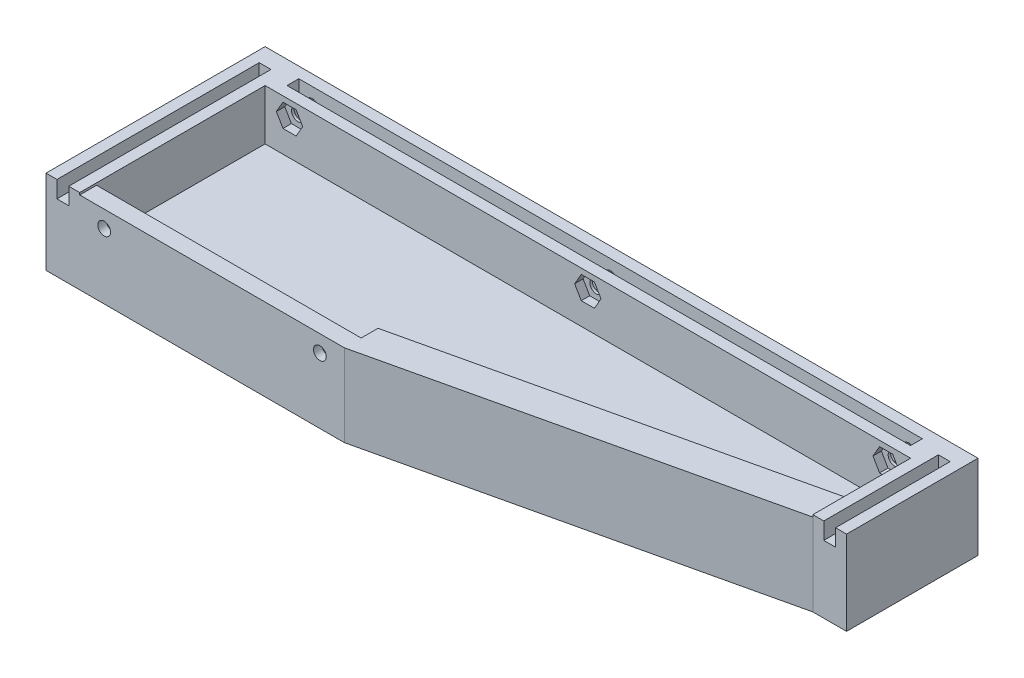
SolidWorks part; units mm, degrees
ref_plane "Front Plane" through (0, 0, 0) normal (1, 0, 0) x (0, 1, 0)
ref_plane "Top Plane" through (0, 0, 0) normal (0, 0, 1) x (0, 1, 0)
ref_plane "Right Plane" through (0, 0, 0) normal (0, 1, 0) x (-1, 0, 0)
sketch "Sketch1" plane through (0, 0, 0) normal (0, 0, 1) x (0, 1, 0)
  line L1 (0, 0) -> (25, 0)
  line L2 (0, 0) -> (0, 211.5)
  line L3 (0, 211.5) -> (25, 211.5)
  line L4 (25, 0) -> (25, 211.5)
  dimension "D1" = 211.5
  dimension "D2" = 25
extrude "Boss-Extrude1" add sketch "Sketch1" along normal blind 10
sketch "Sketch2" plane through (0, 0, 10) normal (0, 0, 1) x (1, 0, 0)
  line L1 (-211.5, 25) -> (-201.5, 25)
  line L2 (-211.5, 25) -> (-211.5, 0)
  line L3 (-211.5, 0) -> (-201.5, 0)
  line L4 (-201.5, 25) -> (-201.5, 0)
  line L5 (0, 0) -> (0, 25) construction
  line L6 (0, 25) -> (-10, 25)
  line L7 (0, 25) -> (0, 0)
  line L8 (0, 0) -> (-10, 0)
  line L9 (-10, 25) -> (-10, 0)
  line L14 (0, 25) -> (-211.5, 25) construction
  line L15 (-211.5, 0) -> (0, 0) construction
  line L17 (-211.5, 0) -> (0, 0)
  line L18 (-211.5, 0) -> (-211.5, 10)
  line L19 (-211.5, 10) -> (0, 10)
  line L20 (0, 0) -> (0, 10)
  line M24 (-211.5, 0) -> (0, 0)
  line M25 (0, 0) -> (0, 25)
  line M26 (0, 25) -> (-211.5, 25)
  line M27 (-211.5, 25) -> (-211.5, 0)
  dimension "D1" = 10
  dimension "D2" = 10
  dimension "D3" = 10
extrude "Boss-Extrude2" add sketch "Sketch2" along normal blind 45 contours L9 L19 L7 M26 | L19 L9 M24 M25 | L19 L4 L9 M24 | L19 L2 L4 M24 | L19 L4 M27 M26
ref_plane "Plane1" through (0, 0, 32.5) normal (0, 0, 1) x (1, 0, 0)
mirror "Mirror1" about plane through (0, 0, 32.5) normal (0, 0, 1) of "Boss-Extrude1"
sketch "Sketch3" plane through (0, 25, 0) normal (0, 1, 0) x (-1, 0, 0)
  line L1 (10, 10) -> (201.5, 10)
  line L2 (10, 10) -> (10, 0)
  line L3 (10, 0) -> (201.5, 0)
  line L4 (201.5, 10) -> (201.5, 0)
  line L5 (13.25, 6.75) -> (13.25, 3.25)
  line L6 (13.25, 3.25) -> (198.25, 3.25)
  line L7 (198.25, 6.75) -> (198.25, 3.25)
  line L8 (13.25, 6.75) -> (198.25, 6.75)
  dimension "D1" = 3.25
extrude "Cut-Extrude1" cut sketch "Sketch3" against normal blind 10 contours L8 L7 L6 L5
sketch "Sketch4" plane through (0, 0, 10) normal (0, 0, 1) x (-1, 0, 0)
  line L1 (201.5, -25) -> (194.25, -25)
  line L2 (201.5, -25) -> (201.5, -20)
  line L3 (201.5, -20) -> (194.25, -20)
  line L4 (194.25, -25) -> (194.25, -20)
  circle A0 centre (194.25, -20) radius 1.9
  dimension "D3" = 3.8
  dimension "D1" = 7.25
  dimension "D2" = 5
extrude "Cut-Extrude2" cut sketch "Sketch4" against normal through all contours A0
sketch "Sketch5" plane through (0, 0, 0) normal (0, 0, -1) x (1, 0, 0)
  circle A0 centre (-194.25, -20) radius 3.35
  dimension "D1" = 6.7
extrude "Cut-Extrude3" cut sketch "Sketch5" against normal blind 2.5
sketch "Sketch6" plane through (0, 0, 10) normal (0, 0, 1) x (1, 0, 0)
  line L0 (-10, 25) -> (-201.5, 25) construction
  line L1 (-192.5, 23.0311) -> (-196, 23.0311)
  line L2 (-196, 23.0311) -> (-197.75, 20)
  line L3 (-197.75, 20) -> (-196, 16.9689)
  line L4 (-196, 16.9689) -> (-192.5, 16.9689)
  line L5 (-192.5, 16.9689) -> (-190.75, 20)
  line L6 (-190.75, 20) -> (-192.5, 23.0311)
  line L7 (-192.2979, 23.3811) -> (-196.2021, 23.3811)
  line L8 (-196.2021, 23.3811) -> (-198.1541, 20)
  line L9 (-198.1541, 20) -> (-196.2021, 16.6189)
  line L10 (-196.2021, 16.6189) -> (-192.2979, 16.6189)
  line L11 (-192.2979, 16.6189) -> (-190.3459, 20)
  line L12 (-190.3459, 20) -> (-192.2979, 23.3811)
  circle A0 centre (-194.25, 20) radius 3.0311 construction
  dimension "D1" = 3.5
  dimension "D2" = 0.35
extrude "Cut-Extrude4" cut sketch "Sketch6" against normal blind 2.5 contours L8 L9 L10 L11 L12 L7
pattern_linear "LPattern1" count 3 spacing 88.5 along (1, 0, 0) of "Cut-Extrude2", "Cut-Extrude3", "Cut-Extrude4"
sketch "Sketch9" plane through (0, 0, 0) normal (0, -1, 0) x (1, 0, 0)
  line L0 (0, 39) -> (-10, 39)
  line L1 (0, 0) -> (-123, 0)
  line L2 (0, 0) -> (0, 39)
  line L3 (0, 39) -> (-123, 39)
  line L4 (-123, 0) -> (-123, 39)
  line L5 (-10, 39) -> (-123, 65)
  line L6 (-211.5, 65) -> (0, 65) construction
  line L7 (-123, 65) -> (-123, 39)
  line M7 (0, 0) -> (0, 65)
  line M8 (0, 65) -> (-211.5, 65)
  dimension "D3" = 10
  dimension "D1" = 39
  dimension "D2" = 123
extrude "Cut-Extrude5" cut sketch "Sketch9" against normal up to next contours L5 L0 M7 M8
sketch "Sketch10" plane through (0, 25, 0) normal (0, 1, 0) x (-1, 0, 0)
  line L0 (123, 65) -> (10, 39)
  line L2 (10, 39) -> (79.5385, 55) construction
  line L5 (123, 65) -> (123, 55)
  line L6 (123, 55) -> (10, 29)
  line L7 (10, 39) -> (10, 10) construction
  line L8 (10, 29) -> (10, 39)
  line L9 (79.5385, 55) -> (201.5, 55) construction
extrude "Boss-Extrude4" add sketch "Sketch10" against normal up to next
sketch "Sketch11" plane through (0, 0, 65) normal (0, 0, 1) x (1, 0, 0)
  line L1 (-211.5, 25) -> (0, 25)
  line L2 (-211.5, 25) -> (-211.5, 24.375)
  line L3 (-211.5, 24.375) -> (0, 24.375)
  line L4 (0, 25) -> (0, 24.375)
  line L6 (-211.5, 25) -> (-201.5, 25)
  line L7 (-211.5, 25) -> (-211.5, 24.375)
  line L8 (-211.5, 24.375) -> (-201.5, 24.375)
  line L9 (-201.5, 25) -> (-201.5, 24.375)
  line L10 (-10, 25) -> (-10, 0) construction
  line L11 (0, 25) -> (-10, 25)
  line L12 (0, 25) -> (0, 24.375)
  line L13 (0, 24.375) -> (-10, 24.375)
  line L14 (-10, 25) -> (-10, 24.375)
  line L15 (0, 25) -> (0, 0) construction
  line M10 (-123, 0) -> (-123, 25)
  line M11 (-123, 25) -> (-211.5, 25)
  dimension "D2" = 10
  dimension "D3" = 10
  dimension "D1" = 0.625
extrude "Cut-Extrude6" cut sketch "Sketch11" against normal up to next contours L9 L3 M11 M10 | L14 L1 L3 M10
sketch "Sketch7" plane through (0, 25, 0) normal (0, 1, 0) x (-1, 0, 0)
  line L0 (0, 39) -> (0, 0) construction
  line L1 (10, 10) -> (0, 10) construction
  line L2 (10, 10) -> (10, 15) construction
  line L3 (10, 15) -> (0, 15) construction
  line L4 (0, 10) -> (0, 15) construction
  line L5 (10, 29) -> (10, 10) construction
  line L6 (0, 15) -> (10, 15)
  line L7 (0, 15) -> (0, 39)
  line L8 (0, 39) -> (10, 39)
  line L9 (10, 15) -> (10, 39)
  line L10 (3.35, 18.35) -> (3.35, 35.65)
  line L11 (3.35, 35.65) -> (6.65, 35.65)
  line L12 (6.65, 18.35) -> (6.65, 35.65)
  line L13 (3.35, 18.35) -> (6.65, 18.35)
  line L15 (3.35, 35.65) -> (6.65, 35.65)
  line L16 (3.35, 35.65) -> (3.35, 39)
  line L17 (3.35, 39) -> (6.65, 39)
  line L18 (6.65, 35.65) -> (6.65, 39)
  dimension "D1" = 5
  dimension "D2" = 24
  dimension "D3" = 3.35
extrude "Boss-Extrude3" [suppressed] add sketch "Sketch7" along normal blind 9.9 contours L11 L18 L8 L16 | L10 L13 L12 L11
sketch "Sketch12" plane through (0, 25, 0) normal (0, 1, 0) x (-1, 0, 0)
  line L1 (0, 10) -> (10, 10) construction
  line L2 (0, 10) -> (0, 15) construction
  line L3 (0, 15) -> (10, 15) construction
  line L4 (10, 10) -> (10, 15) construction
  line L21 (3.25, 5) -> (6.75, 5)
  line L26 (0, 15) -> (3.25, 15)
  line L27 (0, 15) -> (0, 5)
  line L28 (0, 5) -> (3.25, 5)
  line L29 (3.25, 15) -> (3.25, 5)
  line L30 (10, 15) -> (6.75, 15)
  line L31 (10, 15) -> (10, 5)
  line L32 (10, 5) -> (6.75, 5)
  line L33 (6.75, 15) -> (6.75, 5)
  line L34 (3.25, 15) -> (0, 15)
  line L35 (3.25, 15) -> (3.25, 39)
  line L36 (3.25, 39) -> (0, 39)
  line L37 (0, 15) -> (0, 39)
  line L38 (6.75, 15) -> (10, 15)
  line L39 (6.75, 15) -> (6.75, 39)
  line L40 (6.75, 39) -> (10, 39)
  line L41 (10, 15) -> (10, 39)
  line L42 (0, 39) -> (0, 0) construction
  dimension "D3" = 10
  dimension "D1" = 5
  dimension "D2" = 3.25
  dimension "D4" = 3.25
  dimension "D5" = 10
extrude "Cut-Extrude8" cut sketch "Sketch12" against normal blind 5
sketch "Sketch13" plane through (0, 25, 0) normal (0, 1, 0) x (-1, 0, 0)
  line L1 (211.5, 10) -> (201.5, 10) construction
  line L2 (211.5, 10) -> (211.5, 15) construction
  line L3 (211.5, 15) -> (201.5, 15) construction
  line L4 (201.5, 10) -> (201.5, 15) construction
  line L14 (204.75, 5) -> (208.25, 5)
  line L19 (201.5, 15) -> (204.75, 15)
  line L20 (201.5, 15) -> (201.5, 5)
  line L21 (201.5, 5) -> (204.75, 5)
  line L22 (204.75, 15) -> (204.75, 5)
  line L23 (211.5, 15) -> (208.25, 15)
  line L24 (211.5, 15) -> (211.5, 5)
  line L25 (211.5, 5) -> (208.25, 5)
  line L26 (208.25, 15) -> (208.25, 5)
  line L27 (211.5, 65) -> (211.5, 0) construction
  line L28 (204.75, 15) -> (201.5, 15)
  line L29 (204.75, 15) -> (204.75, 65)
  line L30 (204.75, 65) -> (201.5, 65)
  line L31 (201.5, 15) -> (201.5, 65)
  line L32 (208.25, 15) -> (211.5, 15)
  line L33 (208.25, 15) -> (208.25, 65)
  line L34 (208.25, 65) -> (211.5, 65)
  line L35 (211.5, 15) -> (211.5, 65)
  dimension "D1" = 5
  dimension "D2" = 3.25
  dimension "D5" = 10
  dimension "D3" = 3.25
  dimension "D4" = 10
extrude "Cut-Extrude9" cut sketch "Sketch13" against normal blind 5
sketch "Sketch14" plane through (0, 24.375, 0) normal (0, 1, 0) x (-1, 0, 0)
  line L1 (201.5, 55) -> (123, 55)
  line L2 (201.5, 55) -> (201.5, 60)
  line L3 (201.5, 60) -> (123, 60)
  line L4 (123, 55) -> (123, 60)
  dimension "D1" = 5
extrude "Cut-Extrude10" cut sketch "Sketch14" against normal up to surface (14.375 mm away) up to face at (-109.2, 10, 31.8)
sketch "Sketch15" plane through (0, 0, 65) normal (0, 0, 1) x (1, 0, 0)
  line L1 (-201.5, 24.375) -> (-194.25, 24.375)
  line L2 (-201.5, 24.375) -> (-201.5, 19.375)
  line L3 (-201.5, 19.375) -> (-194.25, 19.375)
  line L4 (-194.25, 24.375) -> (-194.25, 19.375)
  circle A0 centre (-194.25, 19.375) radius 1.9
  dimension "D3" = 3.8
  dimension "D1" = 7.25
  dimension "D2" = 5
extrude "Cut-Extrude11" cut sketch "Sketch15" against normal up to next contours A0
sketch "Sketch16" plane through (0, 0, 60) normal (0, 0, -1) x (1, 0, 0)
  line L0 (-201.5, -24.375) -> (-123, -24.375) construction
  line L1 (-192.5, -16.3439) -> (-196, -16.3439)
  line L2 (-196, -16.3439) -> (-197.75, -19.375)
  line L3 (-197.75, -19.375) -> (-196, -22.4061)
  line L4 (-196, -22.4061) -> (-192.5, -22.4061)
  line L5 (-192.5, -22.4061) -> (-190.75, -19.375)
  line L6 (-190.75, -19.375) -> (-192.5, -16.3439)
  line L7 (-192.2979, -15.9939) -> (-196.2021, -15.9939)
  line L8 (-196.2021, -15.9939) -> (-198.1541, -19.375)
  line L9 (-198.1541, -19.375) -> (-196.2021, -22.7561)
  line L10 (-196.2021, -22.7561) -> (-192.2979, -22.7561)
  line L11 (-192.2979, -22.7561) -> (-190.3459, -19.375)
  line L12 (-190.3459, -19.375) -> (-192.2979, -15.9939)
  circle A0 centre (-194.25, -19.375) radius 3.0311 construction
  dimension "D1" = 3.5
  dimension "D2" = 0.35
extrude "Cut-Extrude12" cut sketch "Sketch16" against normal blind 2.5 contours L12 L7 L8 L9 L10 L11
pattern_linear "LPattern2" count 2 spacing 64 along (1, 0, 0) of "Cut-Extrude11", "Cut-Extrude12"
equation "\"whitekey_cutout_length\"= 101.5"
equation "\"key_mount_recess_length\"=50"
equation "\"key_mount_recess_height\"=12.5"
equation "\"key_mount_recess_depth\"=1.5"
equation "\"wall_thickness\"=10"
equation "\"guide_brace_height\"=20"
equation "\"guide_brace_thickness\"=2"
equation "\"dowel_recess_depth\"=10"
equation "\"dowel_recess_offset\"=3.25"
equation "\"dowel_insert_tolerance\"=0.1"
equation "\"base_mount_height\"=40"
equation "\"base_rear_length\"=80"
equation "\"base_front_length\"=111.5"
equation "\"screw_hole_wall_offset\"=7.25"
equation "\"screw_hole_edge_inset\"=\"dowel_recess_depth\"/2"
equation "\"screw_hole_diameter\"=3.8"
equation "\"screw_head_hole_diameter\"=6.7"
equation "\"screw_nut_hole_side_len\"=3.5"
equation "\"screw_nut_recess_offset\"=0.35"
equation "\"screw_head_and_nut_recess_depth\"=2.5"
equation "\"screw_shaft_diameter\"=3.5"
equation "\"switch_board_width\"=30"
equation "\"switch_board_thickness\"=1.6"
equation "\"switch_board_wall_offset\"=11.5"
equation "\"heatset_insert_hole_diameter\"=4.8"
equation "\"heatset_insert_hole_depth\"=3.8"
equation "\"front_rear_panel_width\"=23.75"
equation "\"front_panel_height\"=24"
equation "\"rod_diameter\"=5"
equation "\"rod_head_diameter\"=8"
equation "\"rod_length_adj\"=0.5"
equation "\"rod_insert_length\"=2.8"
equation "\"switch_black_key_mount_height\"=8"
equation "\"switch_white_key_mount_height\"=3"
equation "\"D1@Sketch1\"=\"base_front_length\"+\"base_rear_length\"+\"wall_thickness\"*2"
equation "\"D1@Boss-Extrude1\"=\"wall_thickness\""
equation "\"D2@Sketch2\"=\"wall_thickness\""
equation "\"D1@Sketch2\"=\"wall_thickness\""
equation "\"D3@Sketch2\"=\"wall_thickness\""
equation "\"D1@Sketch3\"=\"dowel_recess_offset\""
equation "\"D1@Cut-Extrude1\"=\"dowel_recess_depth\""
equation "\"D2@Sketch4\"=\"screw_hole_edge_inset\""
equation "\"D1@Sketch4\"=\"screw_hole_wall_offset\""
equation "\"D3@Sketch4\"=\"screw_hole_diameter\""
equation "\"D3@LPattern1\"=0.5*(\"base_front_length\"+\"base_rear_length\"-\"screw_hole_wall_offset\"*2)"
equation "\"D1@Sketch5\"=\"screw_head_hole_diameter\""
equation "\"D1@Cut-Extrude3\"=\"screw_head_and_nut_recess_depth\""
equation "\"D1@Sketch6\"=\"screw_nut_hole_side_len\""
equation "\"D2@Sketch6\"=\"screw_nut_recess_offset\""
equation "\"D1@Cut-Extrude4\"=\"screw_head_and_nut_recess_depth\""
equation "\"D1@Sketch7\"=\"wall_thickness\"/2"
equation "\"D2@Sketch7\"=\"front_panel_height\""
equation "\"D3@Sketch7\"=\"dowel_recess_offset\"+\"dowel_insert_tolerance\""
equation "\"D1@Boss-Extrude3\"=\"dowel_recess_depth\"-\"dowel_insert_tolerance\"*1"
equation "\"D1@Sketch9\"=\"wall_thickness\"*1.5+\"front_panel_height\""
equation "\"D2@Sketch9\"=\"base_front_length\"+\"wall_thickness\"+1.5"
equation "\"D3@Sketch9\"=\"wall_thickness\""
equation "\"D1@Sketch11\"=\"whitekey_spacing\"/2"
equation "\"D2@Sketch11\"=\"wall_thickness\""
equation "\"front_rear_panel_recess_depth\"=5"
equation "\"D1@Sketch12\"=\"wall_thickness\"/2"
equation "\"D5@Sketch12\"=\"dowel_recess_depth\""
equation "\"D3@Sketch12\"=\"dowel_recess_depth\""
equation "\"D2@Sketch12\"=\"dowel_recess_offset\""
equation "\"D4@Sketch12\"=\"dowel_recess_offset\""
equation "\"D1@Cut-Extrude8\"=\"front_rear_panel_recess_depth\""
equation "\"D1@Sketch13\"=\"wall_thickness\"/2"
equation "\"D5@Sketch13\"=\"dowel_recess_depth\""
equation "\"D4@Sketch13\"=\"dowel_recess_depth\""
equation "\"D2@Sketch13\"=\"dowel_recess_offset\""
equation "\"D3@Sketch13\"=\"dowel_recess_offset\""
equation "\"D1@Cut-Extrude9\"=\"front_rear_panel_recess_depth\""
equation "\"D1@Sketch14\"=\"wall_thickness\"/2"
equation "\"D1@Sketch15\"=\"screw_hole_wall_offset\""
equation "\"D2@Sketch15\"=\"screw_hole_edge_inset\""
equation "\"D3@Sketch15\"=\"screw_hole_diameter\""
equation "\"D1@Sketch16\"=\"screw_nut_hole_side_len\""
equation "\"D2@Sketch16\"=\"screw_nut_recess_offset\""
equation "\"D1@Cut-Extrude12\"=\"screw_head_and_nut_recess_depth\""
equation "\"D3@LPattern2\"=\"base_rear_length\"-\"screw_hole_wall_offset\"*2-1.5"
equation "\"D1@Boss-Extrude2\"=\"base_mount_height\"+\"wall_thickness\"/2"
equation "\"whitekey_spacing\"=1.25"
equation "\"side_panel_depth\"=25"
equation "\"D2@Sketch1\"=\"side_panel_depth\""
